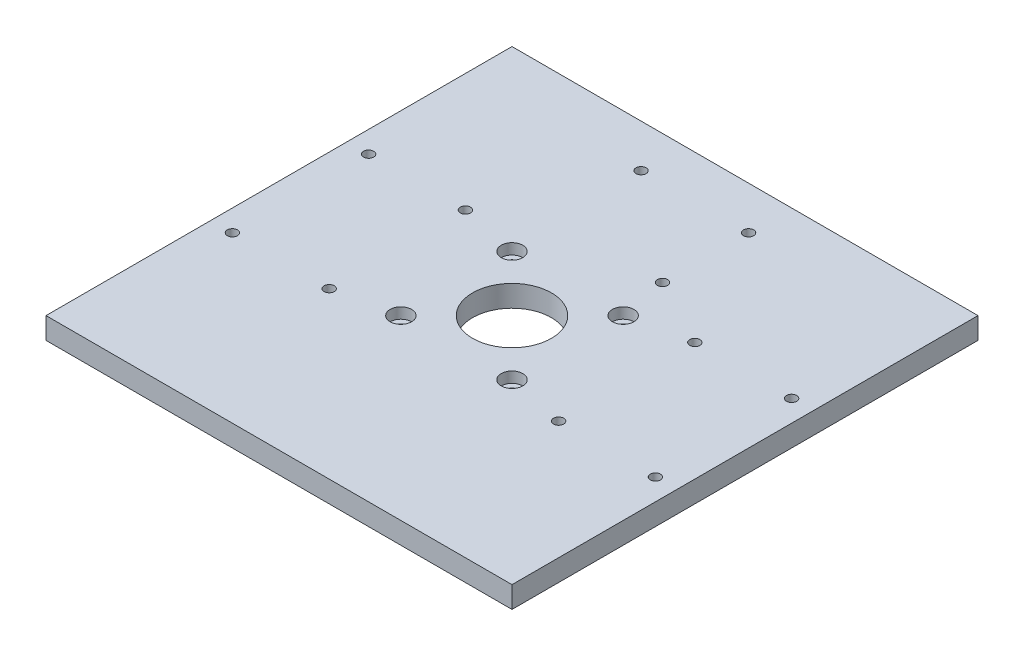
SolidWorks part; units mm, degrees
ref_plane "Front Plane" through (0, 0, 0) normal (0, 0, 1) x (1, 0, 0)
ref_plane "Top Plane" through (0, 0, 0) normal (0, 1, 0) x (1, 0, 0)
ref_plane "Right Plane" through (0, 0, 0) normal (1, 0, 0) x (0, 0, -1)
sketch "Sketch1" plane through (0, 0, 0) normal (0, 1, 0) x (1, 0, 0)
  line L1 (-65, -65) -> (65, -65)
  line L2 (-65, -65) -> (-65, 65)
  line L3 (-65, 65) -> (65, 65)
  line L4 (65, -65) -> (65, 65)
  line L5 (-65, -65) -> (65, 65) construction
  line L6 (-65, 65) -> (65, -65) construction
  circle A0 centre (0, 0) radius 11
  point P0 (0, 0)
  dimension "D3" = 22
  dimension "D1" = 130
  dimension "D2" = 130
extrude "Boss-Extrude1" add sketch "Sketch1" along normal blind 6
sketch "Sketch2" plane through (0, 6, 0) normal (0, 1, 0) x (1, 0, 0)
  line L0 (-15.5, 15.5) -> (15.5, 15.5) construction
  circle A0 centre (-15.5, 15.5) radius 1.42
  circle A1 centre (15.5, 15.5) radius 1.42
  circle A2 centre (15.5, -15.5) radius 1.42
  circle A3 centre (-15.5, -15.5) radius 1.42
  dimension "D1" = 2.84
  dimension "D2" = 15.5
  dimension "D3" = 15.5
  dimension "D6" = 31
  dimension "D4" = 2
  dimension "D5" = 2
extrude "Cut-Extrude1" cut sketch "Sketch2" against normal blind 6
sketch "Sketch3" plane through (0, 6, 0) normal (0, 1, 0) x (1, 0, 0)
  line L0 (-15.5, 15.5) -> (15.5, 15.5) construction
  circle A0 centre (-15.5, 15.5) radius 3
  circle A1 centre (15.5, 15.5) radius 3
  circle A2 centre (15.5, -15.5) radius 3
  circle A3 centre (-15.5, -15.5) radius 3
  dimension "D1" = 6
  dimension "D4" = 31
  dimension "D2" = 2
  dimension "D3" = 2
extrude "Cut-Extrude2" cut sketch "Sketch3" against normal blind 3
sketch "Sketch4" plane through (0, 6, 0) normal (0, 1, 0) x (1, 0, 0)
  line L0 (65, 65) -> (-65, 65) construction
  line L2 (-65, 65) -> (-65, -65) construction
  line L3 (0, 46.5829) -> (0, -60.4578) construction
  circle A0 centre (-59, 19) radius 1.42
  circle A1 centre (-32, 19) radius 1.42
  circle A2 centre (-32, -19) radius 1.42
  circle A3 centre (-59, -19) radius 1.42
  circle A4 centre (59, 19) radius 1.42
  circle A5 centre (59, -19) radius 1.42
  circle A6 centre (32, -19) radius 1.42
  circle A7 centre (32, 19) radius 1.42
  dimension "D1" = 2.84
  dimension "D4" = 46
  dimension "D5" = 6
  dimension "D2" = 2
  dimension "D3" = 2
extrude "Cut-Extrude3" cut sketch "Sketch4" against normal blind 10
sketch "Sketch5" plane through (0, 6, 0) normal (0, 1, 0) x (1, 0, 0)
  line L0 (65, -65) -> (65, 65) construction
  line L1 (65, 65) -> (-65, 65) construction
  circle A0 centre (13, 53) radius 1.42
  circle A1 centre (-17, 53) radius 1.42
  circle A2 centre (13, 29) radius 1.42
  point P10 (0, 0)
  point P11 (13, 29)
  dimension "D2" = 2.84
  dimension "D3" = 2.84
  dimension "D6" = 2.84
  dimension "D1" = 52
  dimension "D4" = 30
  dimension "D5" = 12
  dimension "D7" = 36
extrude "Cut-Extrude4" cut sketch "Sketch5" against normal blind 10
